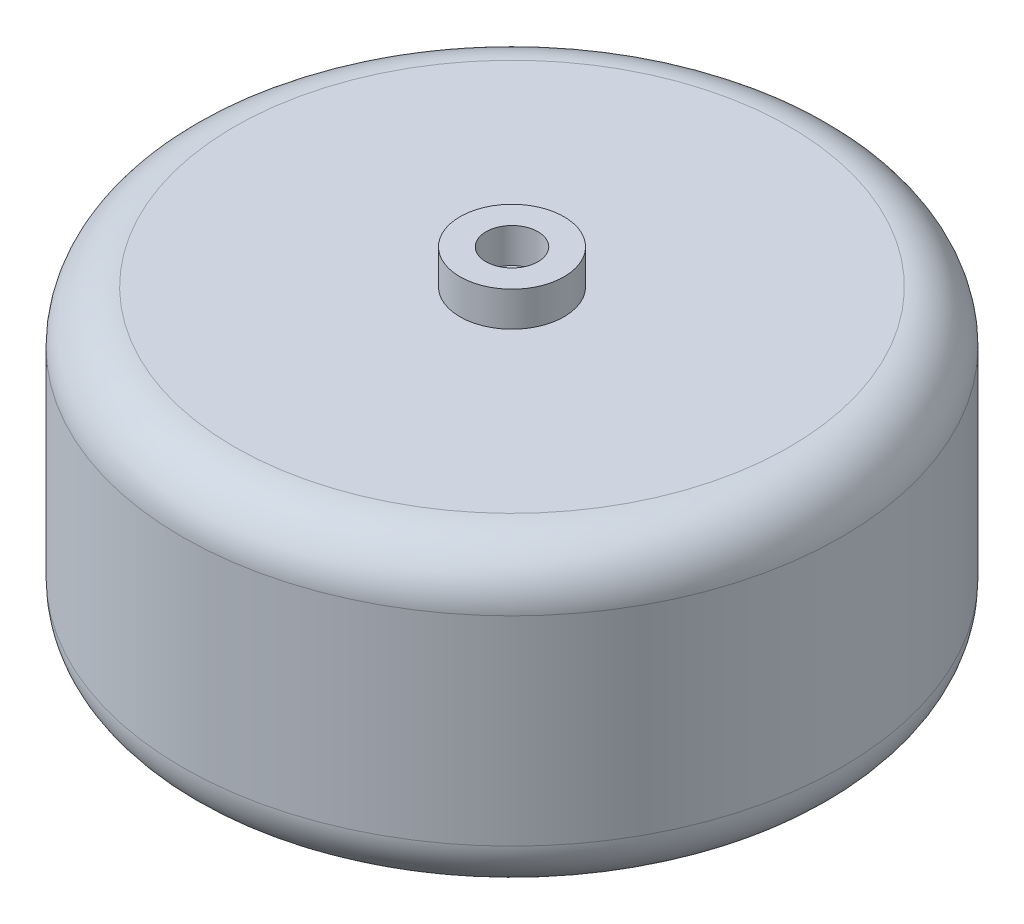
SolidWorks part; units mm, degrees
ref_plane "前视基准面" through (0, 0, 0) normal (0, 0, 1) x (1, 0, 0)
ref_plane "上视基准面" through (0, 0, 0) normal (0, 1, 0) x (1, 0, 0)
ref_plane "右视基准面" through (0, 0, 0) normal (1, 0, 0) x (0, 0, -1)
sketch "草图1" plane through (0, 0, 0) normal (0, 1, 0) x (1, 0, 0)
  circle A0 centre (0, 0) radius 38
  dimension "D1" = 76
extrude "凸台-拉伸1" add sketch "草图1" along normal mid plane 35
sketch "草图2" plane through (0, 17.5, 0) normal (0, 1, 0) x (1, 0, 0)
  circle A0 centre (0, 0) radius 6
  circle A1 centre (0, 0) radius 3
  dimension "D1" = 6
  dimension "D2" = 12
extrude "凸台-拉伸2" add sketch "草图2" along normal blind 4
fillet "圆角1" radius 6 2 edges at (0, 17.5, 38) (0, -17.5, 38)
sketch3d "URDF Reference"
  line L0 (0, 0, 0) -> (10, 0, 0) construction
  line L1 (0, 0, 0) -> (0, 0, -10) construction
  point P0 (0, 0, 0)
